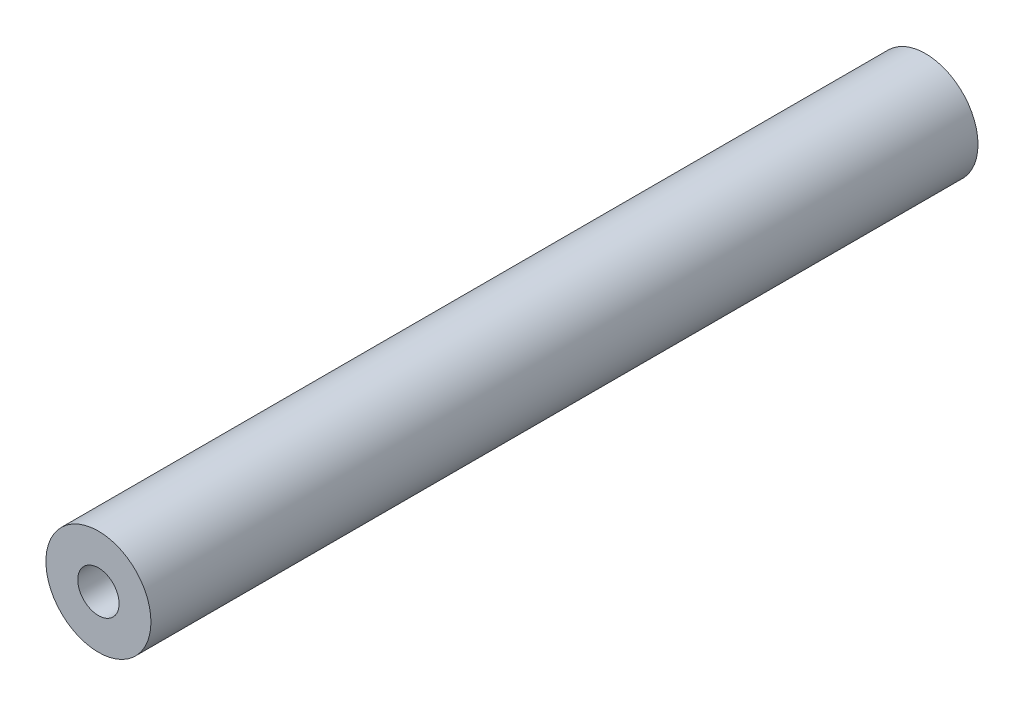
SolidWorks part; units mm, degrees
ref_plane "Alzado" through (0, 0, 0) normal (0, 0, 1) x (1, 0, 0)
ref_plane "Planta" through (0, 0, 0) normal (0, 1, 0) x (1, 0, 0)
ref_plane "Vista lateral" through (0, 0, 0) normal (1, 0, 0) x (0, 0, -1)
sketch "Croquis1" plane through (0, 0, 0) normal (0, 0, 1) x (1, 0, 0)
  circle A0 centre (0, 0) radius 6.35
  dimension "D1" = 12.7
extrude "Saliente-Extruir1" add sketch "Croquis1" along normal mid plane 100
hole_wizard "Taladro roscado M61" positions "Croquis2" profile "Croquis3" tap size "M6" standard "DIN"
sketch "Croquis2" plane through (0, 0, 50) normal (0, 0, 1) x (1, 0, 0)
  point P0 (0, 0)
sketch "Croquis3" plane through (0, 0, 50) normal (1, 0, 0) x (0, -1, 0)
  line L0 (0, 0) -> (0, 18.5022)
  line L1 (0, 18.5022) -> (2.5, 17)
  line L2 (2.5, 17) -> (2.5, 0)
  line L5 (2.5, 0) -> (0, 0)
  line L10 (0, 18.5022) -> (-2.5, 17) construction
  line L11 (0, -6.35) -> (0, 107.95) construction
  dimension "Diámetro de perforador para roscar" = 5
  dimension "Profundidad de perforador para roscar" = 17
  dimension "Ángulo de perforador" = 118
cosmetic thread "Rosca de taladro1" parameters "D1"=12, "D2"=6
mirror "Simetría1" about plane through (0, 0, 0) normal (0, 0, 1) of "Taladro roscado M61"
